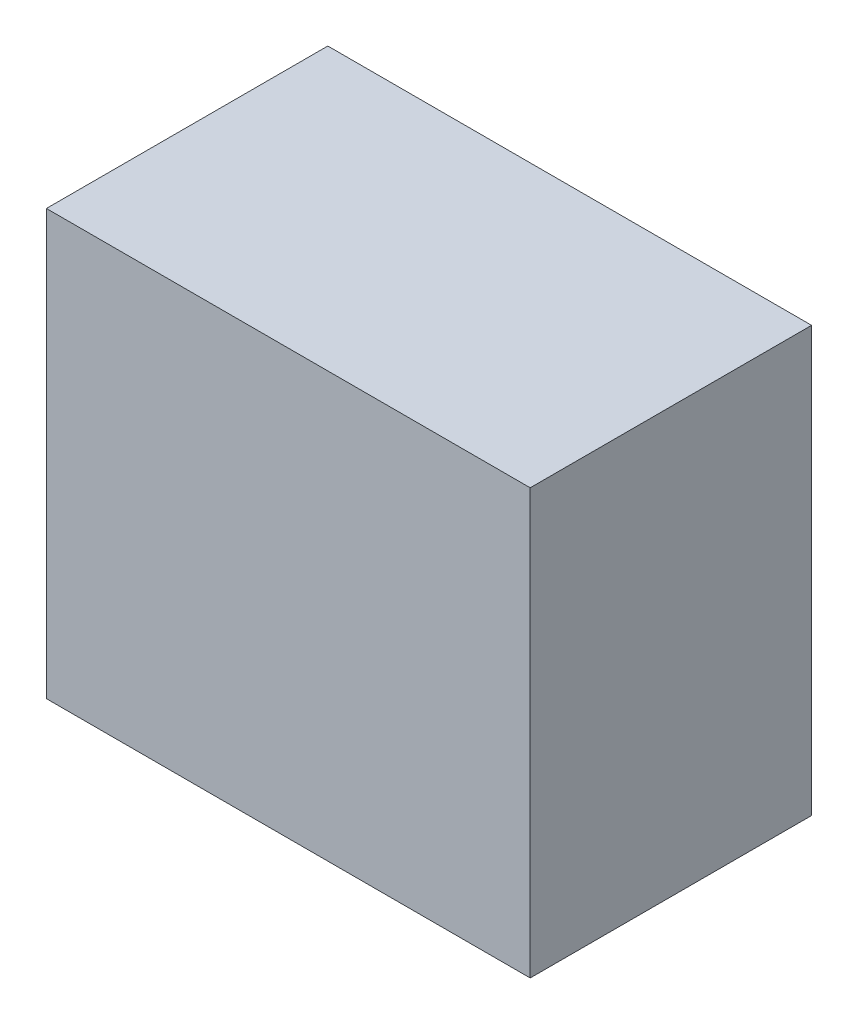
SolidWorks part; units mm, degrees
ref_plane "Front Plane" through (0, 0, 0) normal (0, 0, 1) x (1, 0, 0)
ref_plane "Top Plane" through (0, 0, 0) normal (0, 1, 0) x (1, 0, 0)
ref_plane "Right Plane" through (0, 0, 0) normal (1, 0, 0) x (0, 0, -1)
sketch "Sketch1" plane through (0, 0, 0) normal (0, 1, 0) x (1, 0, 0)
  line L1 (49, -28.5) -> (-49, -28.5)
  line L2 (49, -28.5) -> (49, 28.5)
  line L3 (49, 28.5) -> (-49, 28.5)
  line L4 (-49, -28.5) -> (-49, 28.5)
  line L5 (49, -28.5) -> (-49, 28.5) construction
  line L6 (49, 28.5) -> (-49, -28.5) construction
  point P0 (0, 0)
  dimension "D1" = 98
  dimension "D2" = 57
extrude "Boss-Extrude1" add sketch "Sketch1" along normal mid plane 86
